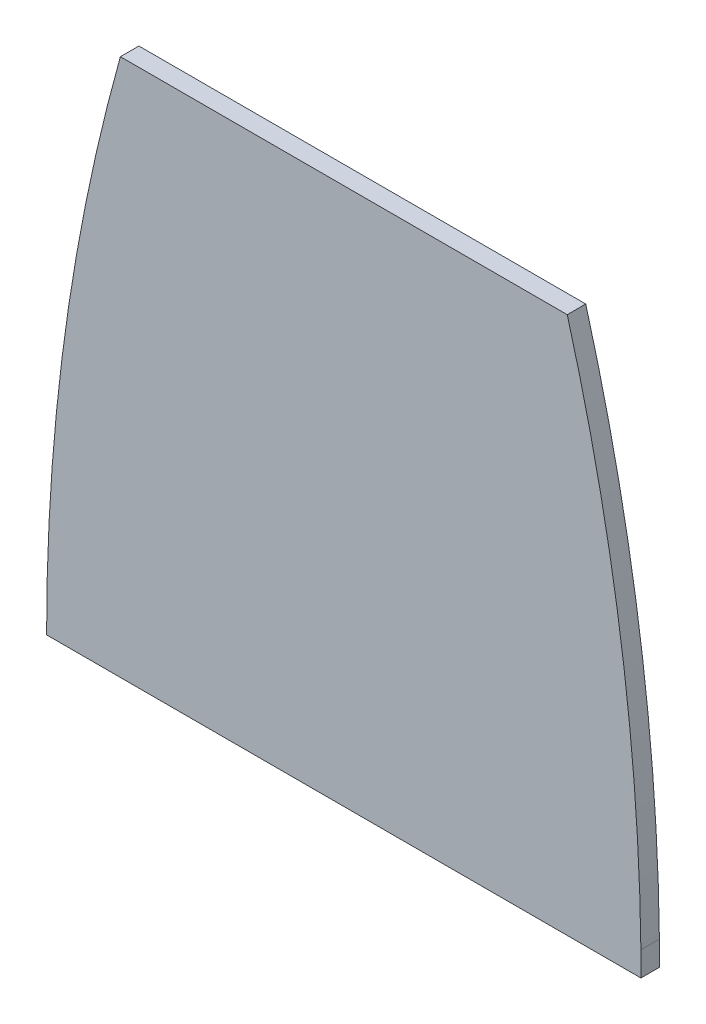
SolidWorks part; units mm, degrees
ref_plane "Спереди" through (0, 0, 0) normal (0, 0, 1) x (1, 0, 0)
ref_plane "Сверху" through (0, 0, 0) normal (0, 1, 0) x (1, 0, 0)
ref_plane "Справа" through (0, 0, 0) normal (1, 0, 0) x (0, 0, -1)
sketch "Эскиз1" plane through (0, 0, 0) normal (0, 0, 1) x (1, 0, 0)
  line L0 (-48.1879, -43.5928) -> (48.1879, -43.5928)
  line L1 (-36.221, 43.5928) -> (36.2453, 43.5928)
  line L2 (48.1879, -43.5928) -> (48.1879, -39.6295)
  arc A0 (48.1879, -39.6295) -> (36.2453, 43.5928) centre (-275.3709, -43.5928) ccw
  arc A1 (-36.221, 43.5928) -> (-48.1879, -43.5928) centre (275.3952, -43.5928) ccw
extrude "Бобышка-Вытянуть1" add sketch "Эскиз1" along normal blind 3 contours L1 A0 L2 L0 A1
